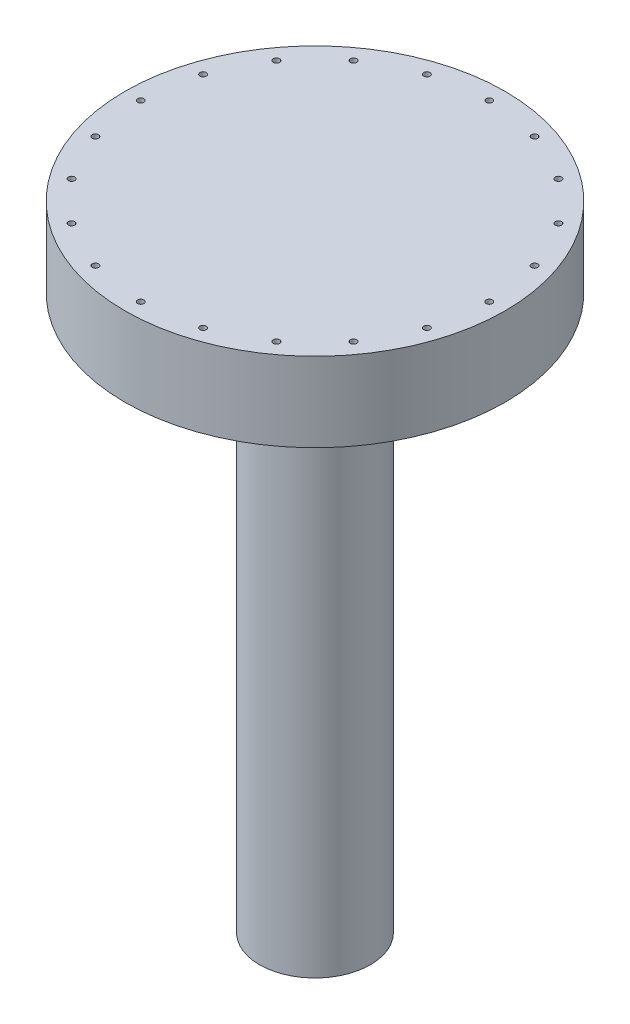
SolidWorks part; units mm, degrees
ref_plane "Front Plane" through (0, 0, 0) normal (0, 0, 1) x (1, 0, 0)
ref_plane "Top Plane" through (0, 0, 0) normal (0, 1, 0) x (1, 0, 0)
ref_plane "Right Plane" through (0, 0, 0) normal (1, 0, 0) x (0, 0, -1)
sketch "Sketch1" plane through (0, 0, 0) normal (0, 1, 0) x (1, 0, 0)
  circle A0 centre (0, 0) radius 3.5
extrude "Boss-Extrude1" add sketch "Sketch1" along normal blind 35
sketch "Sketch2" plane through (0, 35, 0) normal (0, 1, 0) x (1, 0, 0)
  circle A0 centre (0, 0) radius 12
extrude "Boss-Extrude2" add sketch "Sketch2" along normal blind 5
sketch "Sketch3" plane through (0, 40, 0) normal (0, 1, 0) x (1, 0, 0)
  circle A0 centre (0, 11) radius 0.2
  dimension "D1" = 11
extrude "Cut-Extrude1" cut sketch "Sketch3" against normal blind 5
pattern_circular "CirPattern1" count 20 over 360 about axis through (0, 0, 0) along (0, 1, 0) of "Cut-Extrude1"
